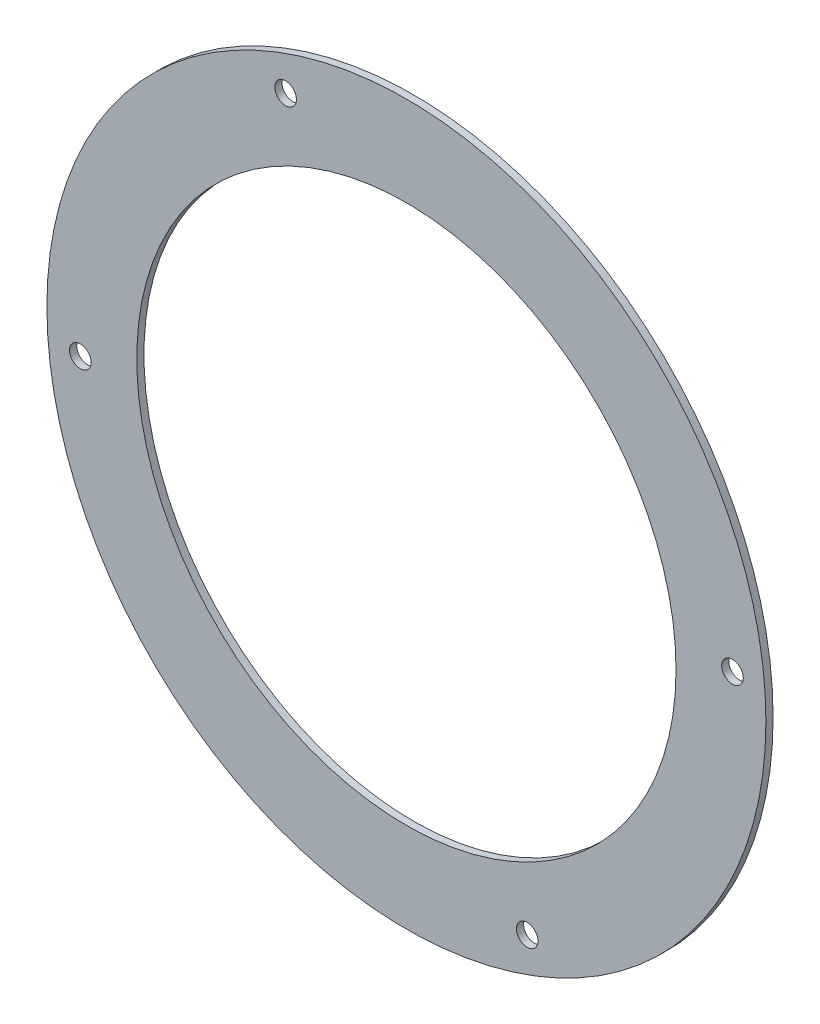
SolidWorks part; units mm, degrees
material "1060 合金"
ref_plane "前视基准面" through (0, 0, 0) normal (0, 0, 1) x (1, 0, 0)
ref_plane "上视基准面" through (0, 0, 0) normal (0, 1, 0) x (1, 0, 0)
ref_plane "右视基准面" through (0, 0, 0) normal (1, 0, 0) x (0, 0, -1)
other "Configuration Table"
sketch "草图1" plane through (0, 0, 0) normal (0, 0, 1) x (1, 0, 0)
  line L0 (-190.1672, -96.2994) -> (-128.0167, -134.9086) construction
  line L5 (-144.8159, -92.6234) -> (-157.7596, -84.5825) construction
  line L7 (-111.3958, -157.6989) -> (-132.8189, -162.7041) construction
  line L9 (-199.79, -150.8518) -> (-218.4776, -139.2426) construction
  line L10 (-111.3958, -157.6989) -> (-132.8189, -162.7041) construction
  line L11 (-122.1073, -160.2015) -> (-134.6828, -106.3767) construction
  circle A0 centre (-144.8159, -92.6234) radius 50
  circle A1 centre (-144.8159, -92.6234) radius 37.5
  circle A2 centre (-190.1672, -96.2994) radius 1.5
  circle A3 centre (-128.0167, -134.9086) radius 1.5
  circle A7 centre (-144.8159, -92.6234) radius 45.5 construction
  circle A8 centre (-99.4646, -88.9475) radius 1.5
  circle A9 centre (-161.6151, -50.3382) radius 1.5
  dimension "D1" = 100
  dimension "75" = 75
  dimension "D3" = 3
  dimension "D5" = 91
extrude "凸台-拉伸1" add sketch "草图1" along normal blind 1 contours A0
